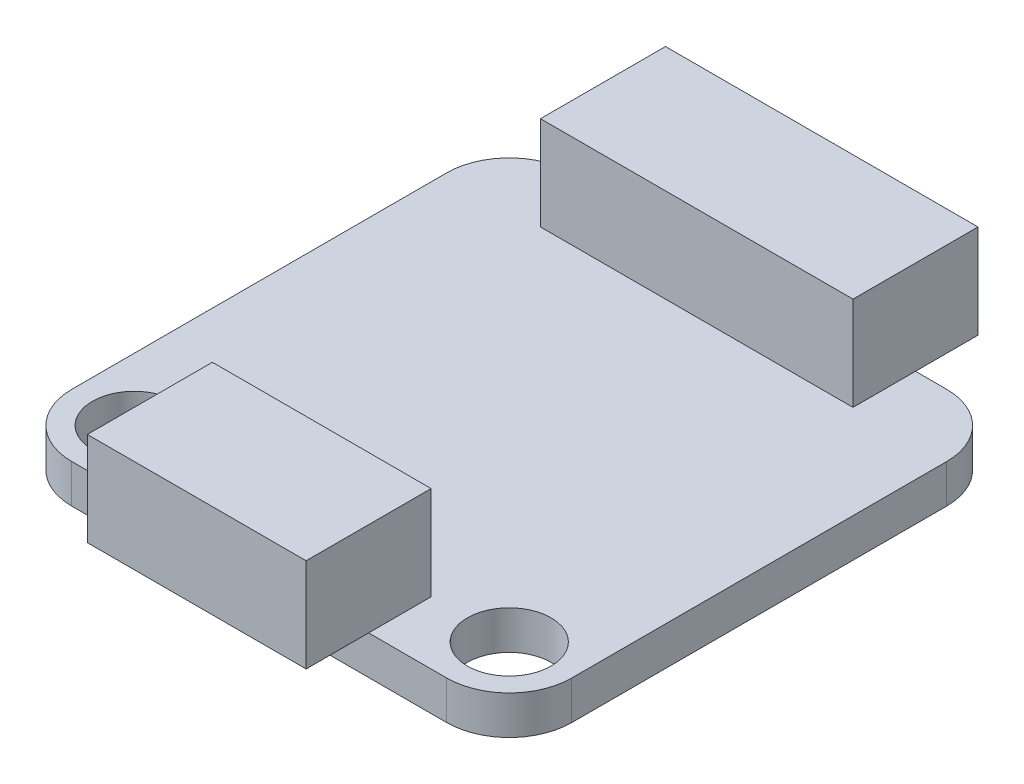
SolidWorks part; units mm, degrees
ref_plane "Front Plane" through (0, 0, 0) normal (0, 0, 1) x (1, 0, 0)
ref_plane "Top Plane" through (0, 0, 0) normal (0, 1, 0) x (1, 0, 0)
ref_plane "Right Plane" through (0, 0, 0) normal (1, 0, 0) x (0, 0, -1)
sketch "Sketch1" plane through (0, 0, 0) normal (0, 1, 0) x (1, 0, 0)
  line L1 (-10.16, -10.16) -> (10.16, -10.16)
  line L2 (-10.16, -10.16) -> (-10.16, 10.16)
  line L3 (-10.16, 10.16) -> (10.16, 10.16)
  line L4 (10.16, -10.16) -> (10.16, 10.16)
  line L5 (-10.16, -10.16) -> (10.16, 10.16) construction
  line L6 (-10.16, 10.16) -> (10.16, -10.16) construction
  point P0 (0, 0)
  dimension "D1" = 20.32
extrude "Boss-Extrude1" add sketch "Sketch1" along normal blind 1.57
fillet "Fillet1" radius 2.54 4 edges at (-10.16, 0.785, -10.16) (10.16, 0.785, -10.16) (10.16, 0.785, 10.16) (-10.16, 0.785, 10.16)
sketch "Sketch2" plane through (0, 1.57, 0) normal (0, 1, 0) x (1, 0, 0)
  line L0 (-7.62, -7.62) -> (7.62, -7.62) construction
  point P0 (-7.62, -7.62)
  point P1 (7.62, -7.62)
hole_wizard "M3 Clearance Hole1" positions "Sketch2" profile "Sketch3" hole size "M3" standard "ANSI Metric" end condition through all
sketch "Sketch3" plane through (-7.62, 1.57, 7.62) normal (1, 0, 0) x (0, 0, 1)
  line L0 (0, 0) -> (0, 1.57)
  line L1 (0, 1.57) -> (1.7, 1.57)
  line L2 (1.7, 1.57) -> (1.7, 0)
  line L5 (1.7, 0) -> (0, 0)
  line L11 (0, -6.35) -> (0, 107.95) construction
  dimension "Thru Hole Dia." = 3.4
  dimension "Thru Hole Depth" = 1.57
sketch "Sketch4" plane through (0, 1.57, 0) normal (0, 1, 0) x (1, 0, 0)
  line L0 (0, 10.16) -> (0, -10.16) construction
  line L1 (7.62, 10.16) -> (-7.62, 10.16) construction
  line L2 (-7.62, -10.16) -> (7.62, -10.16) construction
  line L4 (-4.445, -7.62) -> (4.445, -7.62)
  line L5 (-4.445, -7.62) -> (-4.445, -12.7)
  line L6 (-4.445, -12.7) -> (4.445, -12.7)
  line L7 (4.445, -7.62) -> (4.445, -12.7)
  line L8 (-4.445, -7.62) -> (4.445, -12.7) construction
  line L9 (-4.445, -12.7) -> (4.445, -7.62) construction
  line L10 (-6.35, 7.62) -> (6.35, 7.62)
  line L11 (-6.35, 7.62) -> (-6.35, 12.7)
  line L12 (-6.35, 12.7) -> (6.35, 12.7)
  line L13 (6.35, 7.62) -> (6.35, 12.7)
  line L14 (-6.35, 7.62) -> (6.35, 12.7) construction
  line L15 (-6.35, 12.7) -> (6.35, 7.62) construction
  point P6 (0, -10.16)
  point P12 (0, 10.16)
  dimension "D1" = 5.08
  dimension "D2" = 8.89
  dimension "D3" = 10.16
  dimension "D4" = 5.08
  dimension "D5" = 12.7
  dimension "D6" = 10.16
extrude "Boss-Extrude2" add sketch "Sketch4" along normal blind 3.81 separate body
